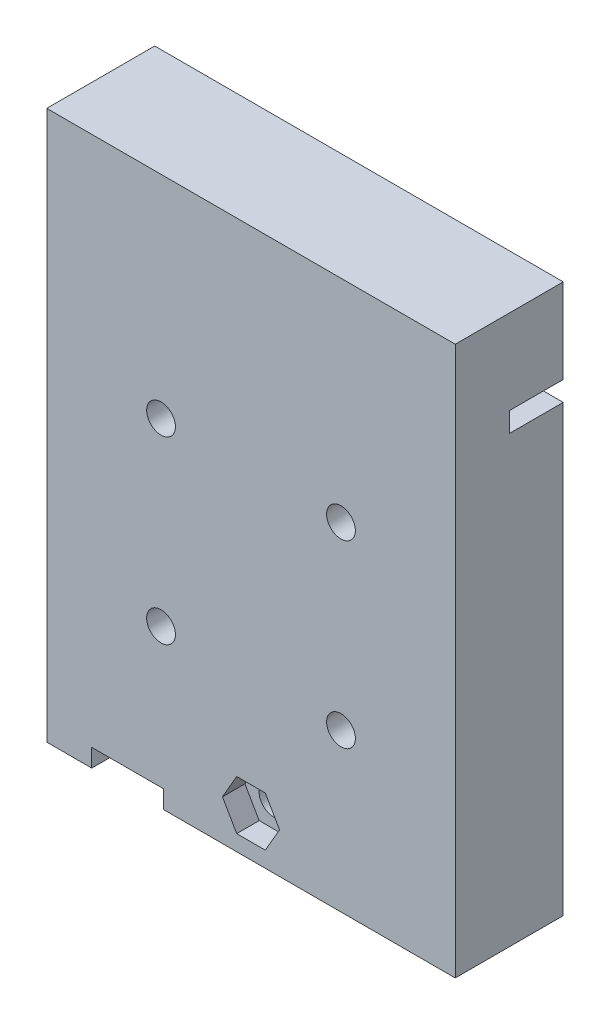
SolidWorks part; units mm, degrees
ref_plane "前视基准面" through (0, 0, 0) normal (0, 0, 1) x (1, 0, 0)
ref_plane "上视基准面" through (0, 0, 0) normal (0, 1, 0) x (1, 0, 0)
ref_plane "右视基准面" through (0, 0, 0) normal (1, 0, 0) x (0, 0, -1)
sketch "草图1" plane through (0, 0, 0) normal (0, 0, 1) x (1, 0, 0)
  line L1 (-54.7963, 27.5425) -> (-9.3963, 27.5425)
  line L2 (-54.7963, 27.5425) -> (-54.7963, 0.5425)
  line L3 (-54.7963, 0.5425) -> (-9.3963, 0.5425)
  line L4 (-9.3963, 27.5425) -> (-9.3963, 0.5425)
  dimension "D1" = 45.4
  dimension "D2" = 27
extrude "凸台-拉伸1" add sketch "草图1" along normal blind 7
sketch "草图2" plane through (0, 0, 0) normal (0, 0, -1) x (-1, 0, 0)
  line L0 (32.0963, 27.5425) -> (32.0963, 0.5425) construction
  line L1 (9.3963, 27.5425) -> (54.7963, 27.5425) construction
  line L2 (54.7963, 0.5425) -> (9.3963, 0.5425) construction
  line L3 (9.3963, 14.0425) -> (54.7963, 14.0425) construction
  line L4 (9.3963, 0.5425) -> (9.3963, 27.5425) construction
  line L5 (54.7963, 27.5425) -> (54.7963, 0.5425) construction
  circle A0 centre (22.0963, 24.0425) radius 1.6
  circle A1 centre (42.0963, 24.0425) radius 1.6
  circle A2 centre (42.0963, 4.0425) radius 1.6
  circle A3 centre (22.0963, 4.0425) radius 1.6
  point P9 (32.0963, 14.0425)
  dimension "D1" = 3.2
  dimension "D2" = 10
  dimension "D3" = 10
extrude "切除-拉伸1" cut sketch "草图2" against normal through all
sketch "草图4" plane through (0, 0, 0) normal (0, 0, -1) x (-1, 0, 0)
  line L0 (38.3463, 0.5425) -> (54.7963, 0.5425)
  line L8 (32.0963, 27.5425) -> (32.0963, 0.5425) construction
  line L9 (9.3963, 14.0425) -> (54.7963, 14.0425) construction
  line L10 (25.8463, 0.5425) -> (25.8463, 4.5425)
  line L11 (9.3963, 27.5425) -> (54.7963, 27.5425)
  line L12 (9.3963, 27.5425) -> (9.3963, 0.5425)
  line L13 (9.3963, 0.5425) -> (25.8463, 0.5425)
  line L14 (54.7963, 27.5425) -> (54.7963, 0.5425)
  line L15 (25.8463, 4.5425) -> (38.3463, 4.5425)
  line L16 (38.3463, 4.5425) -> (38.3463, 0.5425)
  circle A8 centre (42.0963, 24.0425) radius 3.1
  circle A9 centre (22.0963, 24.0425) radius 3.1
  circle A10 centre (22.0963, 24.0425) radius 3.1
  circle A11 centre (42.0963, 4.0425) radius 3.1
  circle A12 centre (22.0963, 4.0425) radius 3.1
  dimension "D2" = 4
  dimension "D3" = 12.5
  dimension "D4" = 6.25
  dimension "D1" = 1.5
extrude "凸台-拉伸2" add sketch "草图4" along normal blind 5
sketch "草图5" plane through (0, 27.5425, 0) normal (0, 1, 0) x (1, 0, 0)
  line L1 (-54.7963, 5) -> (-9.3963, 5)
  line L2 (-54.7963, 5) -> (-54.7963, -7)
  line L3 (-54.7963, -7) -> (-9.3963, -7)
  line L4 (-9.3963, 5) -> (-9.3963, -7)
extrude "凸台-拉伸3" add sketch "草图5" along normal blind 20 contours L2 L3 L4 L1
sketch "草图7" plane through (0, 0, -5) normal (0, 0, -1) x (-1, 0, 0)
  line L0 (9.3963, 27.5425) -> (54.7963, 27.5425) construction
  line L1 (9.3963, 47.5425) -> (9.3963, 0.5425) construction
  line L2 (54.7963, 0.5425) -> (54.7963, 47.5425) construction
  line L3 (9.3963, 0.5425) -> (25.8463, 0.5425) construction
  line L4 (9.3963, 37.0425) -> (54.7963, 37.0425) construction
  line L5 (32.0963, 47.5425) -> (32.0963, 27.5425) construction
  line L6 (54.7963, 47.5425) -> (9.3963, 47.5425) construction
  line L7 (9.3963, 38.1425) -> (16.3755, 38.1425)
  line L8 (9.3963, 35.9425) -> (16.3755, 35.9425)
  line L9 (9.3963, 38.1425) -> (9.3963, 35.9425)
  line L10 (54.7963, 35.9425) -> (47.8172, 35.9425)
  line L11 (54.7963, 38.1425) -> (47.8172, 38.1425)
  line L12 (54.7963, 38.1425) -> (54.7963, 35.9425)
  circle A0 centre (25.4963, 37.0425) radius 5
  circle A1 centre (38.6963, 37.0425) radius 5
  arc A2 (31.2713, 40.9984) -> (19.1117, 39.9125) centre (25.4963, 37.0425) ccw
  arc A3 (32.9213, 40.9984) -> (45.0809, 39.9125) centre (38.6963, 37.0425) cw
  arc A4 (19.1117, 34.1725) -> (31.2713, 33.0866) centre (25.4963, 37.0425) ccw
  circle A5 centre (38.6963, 37.0425) radius 7 construction
  circle A6 centre (25.4963, 37.0425) radius 7 construction
  arc A7 (45.0809, 34.1725) -> (32.9213, 33.0866) centre (38.6963, 37.0425) cw
  arc A8 (47.8172, 35.9425) -> (45.0809, 34.1725) centre (47.8172, 32.9425) ccw
  arc A9 (47.8172, 38.1425) -> (45.0809, 39.9125) centre (47.8172, 41.1425) cw
  arc A10 (16.3755, 35.9425) -> (19.1117, 34.1725) centre (16.3755, 32.9425) cw
  arc A11 (16.3755, 38.1425) -> (19.1117, 39.9125) centre (16.3755, 41.1425) ccw
  arc A12 (32.9213, 33.0866) -> (31.2713, 33.0866) centre (32.0963, 32.5215) ccw
  arc A13 (32.9213, 40.9984) -> (31.2713, 40.9984) centre (32.0963, 41.5636) cw
  point P22 (45.6963, 37.0425)
  point P25 (32.4963, 37.0425)
  point P36 (45.6094, 35.9425)
  point P39 (45.6094, 38.1425)
  point P42 (18.5833, 35.9425)
  point P45 (18.5833, 38.1425)
  point P48 (32.0963, 34.7101)
  point P51 (32.0963, 39.3749)
  dimension "D3" = 10
  dimension "D4" = 6.6
  dimension "D7" = 3
  dimension "D8" = 1
  dimension "D1" = 27
  dimension "D2" = 9.5
  dimension "D6" = 1.1
  dimension "D5" = 2
extrude "切除-拉伸3" cut sketch "草图7" against normal blind 6
sketch "草图8" plane through (0, 0.5425, 0) normal (0, -1, 0) x (1, 0, 0)
  line L0 (-38.3463, -5) -> (-38.3463, 0)
  line L1 (-54.7963, 7) -> (-9.3963, 7)
  line L2 (-54.7963, 7) -> (-54.7963, -5)
  line L3 (-54.7963, -5) -> (-38.3463, -5)
  line L4 (-9.3963, 7) -> (-9.3963, -5)
  line L5 (-38.3463, 0) -> (-25.8463, 0)
  line L6 (-25.8463, 0) -> (-25.8463, -5)
  line L7 (-25.8463, -5) -> (-9.3963, -5)
extrude "凸台-拉伸4" add sketch "草图8" along normal blind 14
sketch "草图9" plane through (0, 0, 7) normal (0, 0, 1) x (1, 0, 0)
  line L0 (-54.7963, 0.5425) -> (-9.3963, 0.5425) construction
  circle A0 centre (-32.0963, -8.9575) radius 1.6
  dimension "D1" = 3.2
  dimension "D2" = 9.5
extrude "切除-拉伸4" cut sketch "草图9" against normal through all
sketch "草图3" plane through (0, 0, 7) normal (0, 0, 1) x (1, 0, 0)
  line L1 (-28.9209, -8.9575) -> (-30.5086, -6.2075)
  line L2 (-30.5086, -6.2075) -> (-33.684, -6.2075)
  line L3 (-33.684, -6.2075) -> (-35.2717, -8.9575)
  line L4 (-35.2717, -8.9575) -> (-33.684, -11.7075)
  line L5 (-33.684, -11.7075) -> (-30.5086, -11.7075)
  line L6 (-30.5086, -11.7075) -> (-28.9209, -8.9575)
  circle A0 centre (-32.0963, -8.9575) radius 2.75 construction
  dimension "D1" = 5.5
extrude "切除-拉伸5" cut sketch "草图3" against normal blind 2.5 contours L2 L3 L4 L5 L6 L1
sketch "草图10" plane through (0, -13.4575, 0) normal (0, -1, 0) x (1, 0, 0)
  line L0 (-9.3963, 7) -> (-54.7963, 7) construction
  line L1 (-49.7963, 7) -> (-41.7963, 7)
  line L2 (-49.7963, 7) -> (-49.7963, -5)
  line L3 (-49.7963, -5) -> (-41.7963, -5)
  line L4 (-41.7963, 7) -> (-41.7963, -5)
  line L5 (-54.7963, 7) -> (-54.7963, -5) construction
  dimension "D1" = 5
  dimension "D2" = 12
  dimension "D3" = 8
extrude "切除-拉伸6" cut sketch "草图10" against normal blind 2
sketch "草图12" plane through (0, -11.4575, 0) normal (0, -1, 0) x (1, 0, 0)
  circle A0 centre (-45.7963, 1) radius 2.2
  dimension "D1" = 4.4
extrude "切除-拉伸8" cut sketch "草图12" against normal blind 6
sketch "草图13" plane through (0, 0, -5) normal (0, 0, -1) x (-1, 0, 0)
  line L0 (22.0963, 24.0425) -> (22.0963, 4.0425) construction
  circle A0 centre (32.0963, 14.0425) radius 2.2
  dimension "D1" = 4.4
extrude "切除-拉伸9" cut sketch "草图13" against normal blind 6
